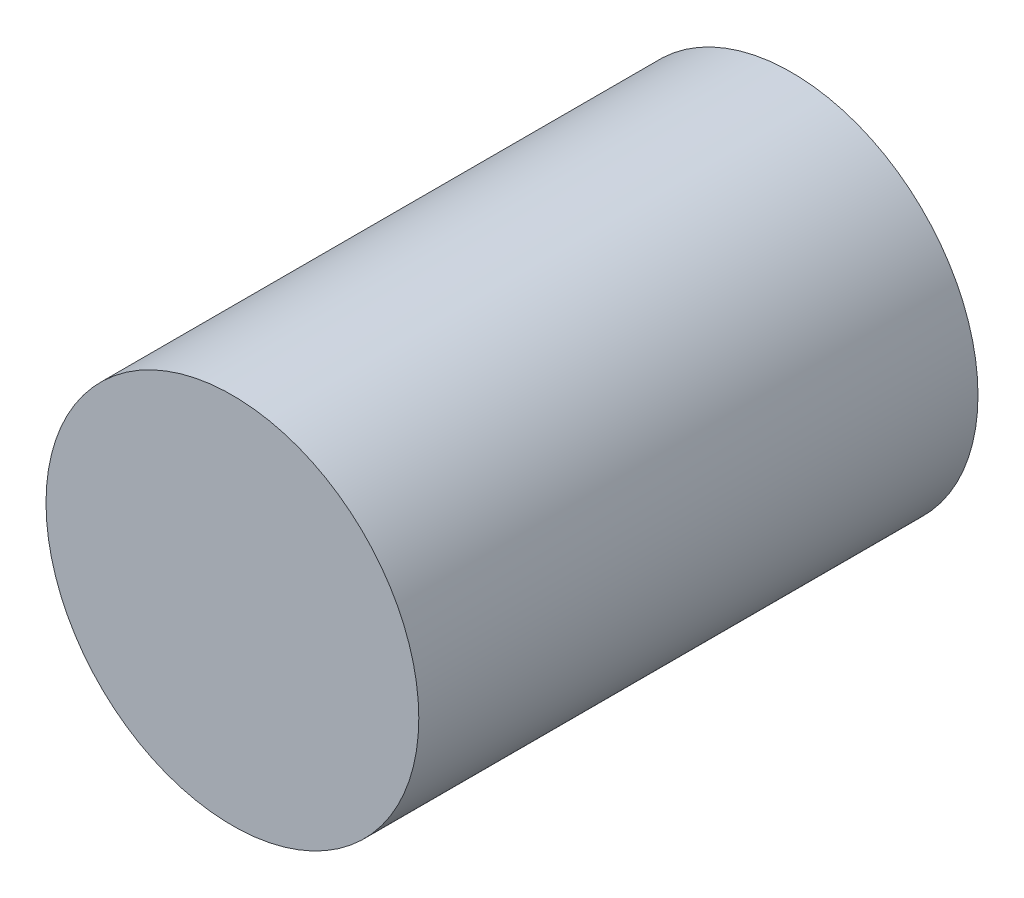
SolidWorks part; units mm, degrees
ref_plane "前视基准面" through (0, 0, 0) normal (0, 0, 1) x (1, 0, 0)
ref_plane "上视基准面" through (0, 0, 0) normal (0, 1, 0) x (1, 0, 0)
ref_plane "右视基准面" through (0, 0, 0) normal (1, 0, 0) x (0, 0, -1)
other "Configuration Table"
sketch "草图1" plane through (0, 0, 0) normal (0, 0, 1) x (1, 0, 0)
  circle A0 centre (0, 0) radius 9
extrude "凸台-拉伸2" add sketch "草图1" along normal blind 27 contours A0
